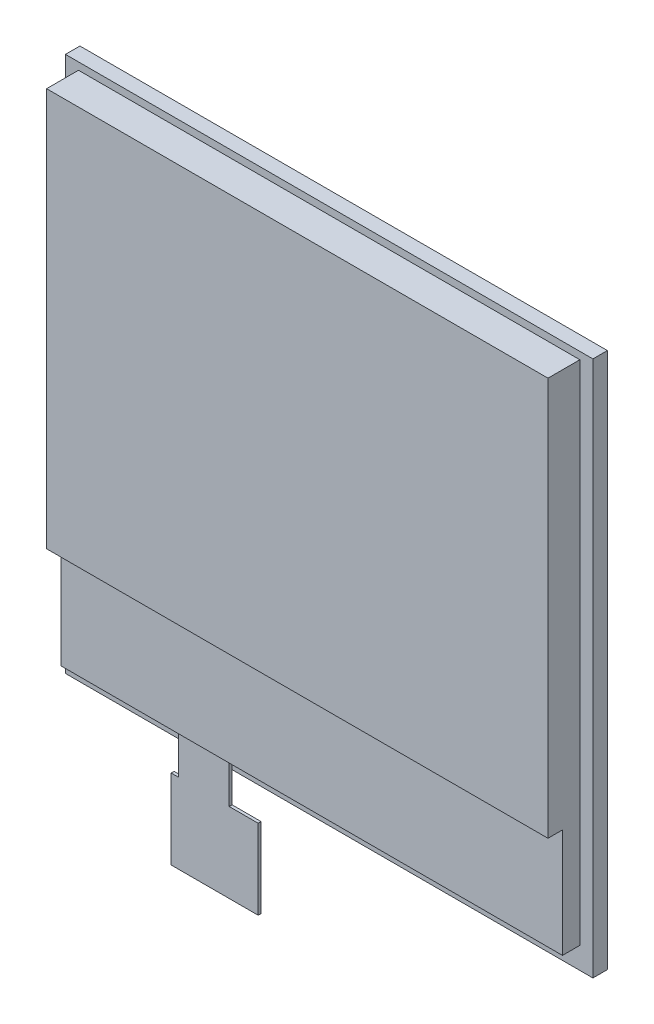
SolidWorks part; units mm, degrees
ref_plane "Front Plane" through (0, 0, 0) normal (0, 0, 1) x (1, 0, 0)
ref_plane "Top Plane" through (0, 0, 0) normal (0, 1, 0) x (1, 0, 0)
ref_plane "Right Plane" through (0, 0, 0) normal (1, 0, 0) x (0, 0, -1)
sketch "Sketch1" plane through (0, 0, 0) normal (0, 0, 1) x (1, 0, 0)
  line L1 (-18.2, 18.5) -> (18.2, 18.5)
  line L2 (-18.2, 18.5) -> (-18.2, -18.5)
  line L3 (-18.2, -18.5) -> (18.2, -18.5)
  line L4 (18.2, 18.5) -> (18.2, -18.5)
  line L5 (-18.2, 18.5) -> (18.2, -18.5) construction
  line L6 (-18.2, -18.5) -> (18.2, 18.5) construction
  point P0 (0, 0)
  dimension "D1" = 36.4
  dimension "D2" = 37
extrude "Boss-Extrude1" add sketch "Sketch1" along normal blind 1
sketch "Sketch2" plane through (0, 0, 1) normal (0, 0, 1) x (1, 0, 0)
  line L0 (0, 0) -> (0, 4.25) construction
  line L1 (-17.3, 18) -> (17.3, 18)
  line L2 (-17.3, 18) -> (-17.3, -9.5)
  line L3 (-17.3, -9.5) -> (17.3, -9.5)
  line L4 (17.3, 18) -> (17.3, -9.5)
  line L5 (-17.3, 18) -> (17.3, -9.5) construction
  line L6 (-17.3, -9.5) -> (17.3, 18) construction
  line L7 (18.2, 18.5) -> (-18.2, 18.5) construction
  point P0 (0, 4.25)
  dimension "D1" = 34.6
  dimension "D2" = 27.5
  dimension "D3" = 0.5
extrude "Boss-Extrude2" add sketch "Sketch2" along normal blind 2.2
sketch "Sketch3" plane through (0, 0, 1) normal (0, 0, 1) x (1, 0, 0)
  line L0 (-18.2, -18.5) -> (18.2, -18.5) construction
  line L1 (-17.3, -9.5) -> (17.3, -9.5)
  line L2 (-17.3, -9.5) -> (-17.3, -17)
  line L3 (-17.3, -17) -> (17.3, -17)
  line L4 (17.3, -9.5) -> (17.3, -17)
  dimension "D1" = 1.5
extrude "Boss-Extrude3" add sketch "Sketch3" along normal blind 1.2
sketch "Sketch4" plane through (0, 0, 1) normal (0, 0, 1) x (1, 0, 0)
  line L0 (-10.2, -17) -> (-6.7, -17)
  line L1 (-17.3, -17) -> (17.3, -17) construction
  line L2 (-6.7, -17) -> (-6.7, -20.6)
  line L3 (-6.7, -20.6) -> (-4.7, -20.6)
  line L4 (-4.7, -20.6) -> (-4.7, -26.1)
  line L5 (-4.7, -26.1) -> (-10.7, -26.1)
  line L6 (-10.7, -26.1) -> (-10.7, -20.6)
  line L7 (-10.7, -20.6) -> (-10.2, -20.6)
  line L8 (-10.2, -20.6) -> (-10.2, -17)
  line L9 (-18.2, -18.5) -> (18.2, -18.5) construction
  line L10 (-18.2, 18.5) -> (-18.2, -18.5) construction
  dimension "D1" = 6
  dimension "D2" = 5.5
  dimension "D3" = 7.6
  dimension "D4" = 13.5
  dimension "D5" = 0.5
  dimension "D6" = 2
extrude "Boss-Extrude4" add sketch "Sketch4" along normal blind 0.2
sketch "Sketch5" plane through (0, 0, 1) normal (0, 0, -1) x (-1, 0, 0)
  line L0 (7.7, -22.1) -> (7.7, -21.6) construction
  line L1 (6.2, -21.6) -> (9.2, -21.6)
  line L2 (6.2, -21.6) -> (6.2, -25.1)
  line L3 (6.2, -25.1) -> (9.2, -25.1)
  line L4 (9.2, -21.6) -> (9.2, -25.1)
  line L5 (6.9, -22.1) -> (8.5, -22.1)
  line L6 (6.9, -22.1) -> (6.9, -24.6)
  line L7 (6.9, -24.6) -> (8.5, -24.6)
  line L8 (8.5, -22.1) -> (8.5, -24.6)
  line L9 (7.7, -25.1) -> (7.7, -26.1) construction
  line L10 (10.7, -26.1) -> (4.7, -26.1) construction
  line L11 (10.2, -20.6) -> (10.7, -20.6) construction
  line L12 (7.7, -25.1) -> (7.7, -24.6) construction
  dimension "D1" = 3
  dimension "D2" = 1
  dimension "D3" = 1
  dimension "D4" = 0.5
  dimension "D5" = 0.7
extrude "Boss-Extrude5" add sketch "Sketch5" along normal blind 0.9
